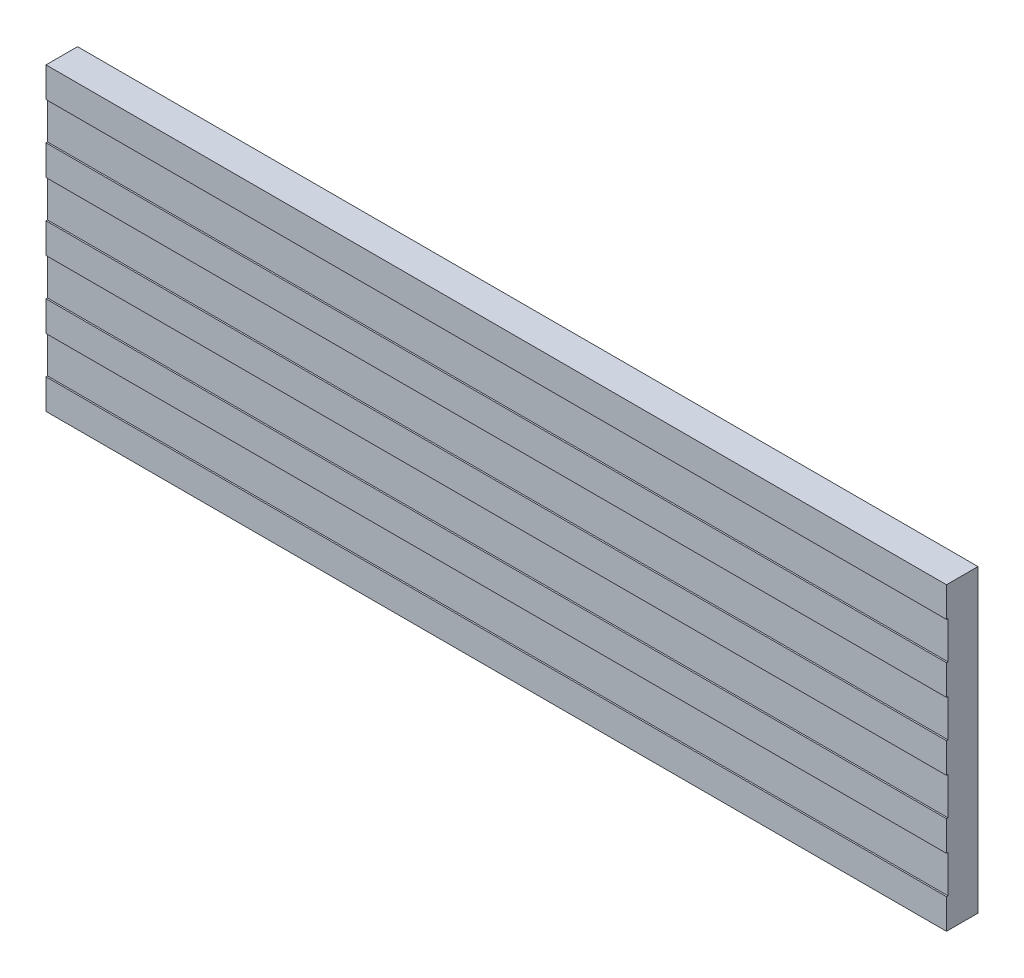
SolidWorks part; units mm, degrees
ref_plane "Plan de face" through (0, 0, 0) normal (0, 0, 1) x (1, 0, 0)
ref_plane "Plan de dessus" through (0, 0, 0) normal (0, 1, 0) x (1, 0, 0)
ref_plane "Plan de droite" through (0, 0, 0) normal (1, 0, 0) x (0, 0, -1)
sketch "Esquisse1" plane through (0, 0, 0) normal (0, 0, 1) x (1, 0, 0)
  line L1 (-45.0099, 19.9904) -> (554.9901, 19.9904)
  line L2 (-45.0099, 19.9904) -> (-45.0099, -180.0096)
  line L3 (-45.0099, -180.0096) -> (554.9901, -180.0096)
  line L4 (554.9901, 19.9904) -> (554.9901, -180.0096)
  dimension "D1" = 600
  dimension "D2" = 200
extrude "Boss.-Extru.1" add sketch "Esquisse1" along normal blind 20
sketch "Esquisse2" plane through (0, 0, 20) normal (0, 0, 1) x (1, 0, 0)
  line L0 (554.9901, -180.0096) -> (554.9901, 19.9904) construction
  line L1 (-45.0099, 19.9904) -> (554.9901, 19.9904)
  line L2 (-45.0099, 19.9904) -> (-45.0099, -0.0096)
  line L3 (-45.0099, -0.0096) -> (554.9901, -0.0096)
  line L4 (554.9901, 19.9904) -> (554.9901, -0.0096)
  line L5 (-45.0099, 19.9904) -> (-45.0099, -180.0096) construction
  line L6 (554.9901, -25.0096) -> (-45.0099, -25.0096)
  line L7 (554.9901, -25.0096) -> (554.9901, -45.0096)
  line L8 (554.9901, -45.0096) -> (-45.0099, -45.0096)
  line L9 (-45.0099, -25.0096) -> (-45.0099, -45.0096)
  line L11 (-45.0099, -70.0096) -> (554.9901, -70.0096)
  line L12 (-45.0099, -70.0096) -> (-45.0099, -90.0096)
  line L13 (-45.0099, -90.0096) -> (554.9901, -90.0096)
  line L14 (554.9901, -70.0096) -> (554.9901, -90.0096)
  line L15 (-45.0099, -115.0096) -> (554.9901, -115.0096)
  line L16 (-45.0099, -115.0096) -> (-45.0099, -135.0096)
  line L17 (-45.0099, -135.0096) -> (554.9901, -135.0096)
  line L18 (554.9901, -115.0096) -> (554.9901, -135.0096)
  line L19 (554.9901, -180.0096) -> (-45.0099, -180.0096)
  line L20 (554.9901, -180.0096) -> (554.9901, -160.0096)
  line L21 (554.9901, -160.0096) -> (-45.0099, -160.0096)
  line L22 (-45.0099, -180.0096) -> (-45.0099, -160.0096)
  dimension "D1" = 20
  dimension "D2" = 20
  dimension "D3" = 20
  dimension "D4" = 20
  dimension "D5" = 20
  dimension "D6" = 25
  dimension "D7" = 25
  dimension "D8" = 25
  dimension "D9" = 25
extrude "Boss.-Extru.2" add sketch "Esquisse2" along normal blind 1
